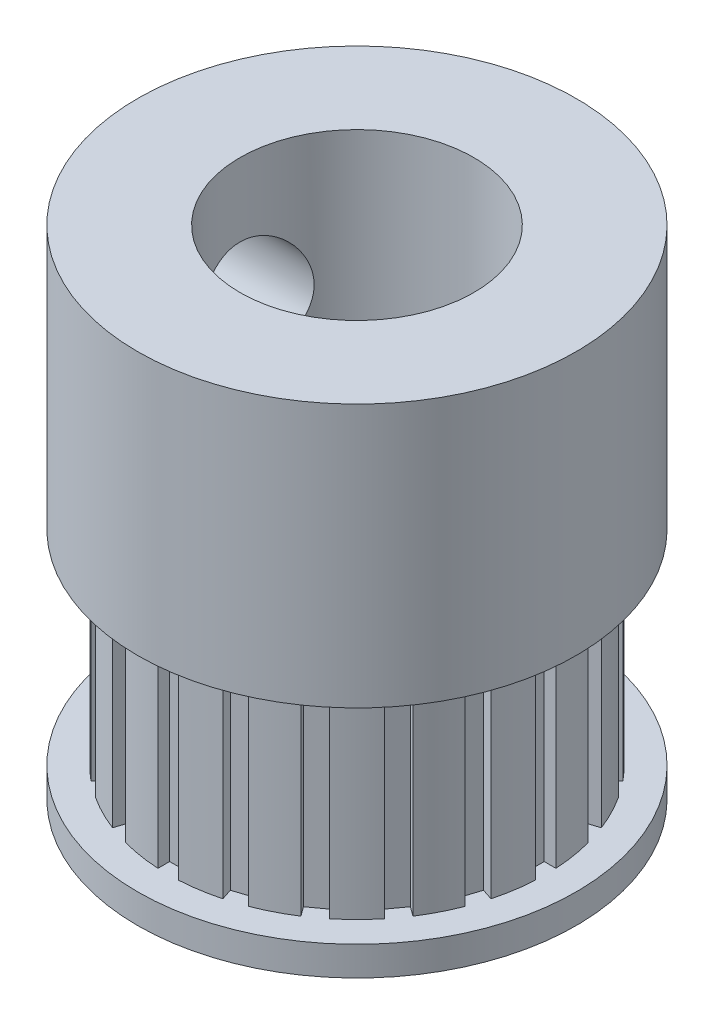
SolidWorks part; units mm, degrees
ref_plane "前视" through (0, 0, 0) normal (0, 0, 1) x (1, 0, 0)
ref_plane "上视" through (0, 0, 0) normal (0, 1, 0) x (1, 0, 0)
ref_plane "右视" through (0, 0, 0) normal (1, 0, 0) x (0, 0, -1)
sketch "草图1" plane through (0, 0, 0) normal (0, 1, 0) x (1, 0, 0)
  circle A0 centre (0, 0) radius 7.5
  dimension "D1" = 15
extrude "凸台-拉伸1" add sketch "草图1" along normal blind 1
sketch "草图2" plane through (0, 1, 0) normal (0, 1, 0) x (1, 0, 0)
  line L0 (-0.35, 6.4555) -> (-0.35, 6.0555)
  line L1 (0.35, 6.4555) -> (0.35, 6.0555)
  line L2 (0.35, 6.0555) -> (-0.35, 6.0555)
  line L3 (1.662, 6.2477) -> (1.5384, 5.8673)
  line L4 (2.2041, 5.651) -> (1.5384, 5.8673)
  line L5 (2.3277, 6.0314) -> (2.2041, 5.651)
  line L6 (3.5113, 5.4283) -> (3.2762, 5.1047)
  line L7 (3.8425, 4.6933) -> (3.2762, 5.1047)
  line L8 (4.0776, 5.0169) -> (3.8425, 4.6933)
  line L9 (5.0169, 4.0776) -> (4.6933, 3.8425)
  line L10 (5.1047, 3.2762) -> (4.6933, 3.8425)
  line L11 (5.4283, 3.5113) -> (5.1047, 3.2762)
  line L12 (6.0314, 2.3277) -> (5.651, 2.2041)
  line L13 (5.8673, 1.5384) -> (5.651, 2.2041)
  line L14 (6.2477, 1.662) -> (5.8673, 1.5384)
  line L15 (6.4555, 0.35) -> (6.0555, 0.35)
  line L16 (6.0555, -0.35) -> (6.0555, 0.35)
  line L17 (6.4555, -0.35) -> (6.0555, -0.35)
  line L18 (6.2477, -1.662) -> (5.8673, -1.5384)
  line L19 (5.651, -2.2041) -> (5.8673, -1.5384)
  line L20 (6.0314, -2.3277) -> (5.651, -2.2041)
  line L21 (5.4283, -3.5113) -> (5.1047, -3.2762)
  line L22 (4.6933, -3.8425) -> (5.1047, -3.2762)
  line L23 (5.0169, -4.0776) -> (4.6933, -3.8425)
  line L24 (4.0776, -5.0169) -> (3.8425, -4.6933)
  line L25 (3.2762, -5.1047) -> (3.8425, -4.6933)
  line L26 (3.5113, -5.4283) -> (3.2762, -5.1047)
  line L27 (2.3277, -6.0314) -> (2.2041, -5.651)
  line L28 (1.5384, -5.8673) -> (2.2041, -5.651)
  line L29 (1.662, -6.2477) -> (1.5384, -5.8673)
  line L30 (0.35, -6.4555) -> (0.35, -6.0555)
  line L31 (-0.35, -6.0555) -> (0.35, -6.0555)
  line L32 (-0.35, -6.4555) -> (-0.35, -6.0555)
  line L33 (-1.662, -6.2477) -> (-1.5384, -5.8673)
  line L34 (-2.2041, -5.651) -> (-1.5384, -5.8673)
  line L35 (-2.3277, -6.0314) -> (-2.2041, -5.651)
  line L36 (-3.5113, -5.4283) -> (-3.2762, -5.1047)
  line L37 (-3.8425, -4.6933) -> (-3.2762, -5.1047)
  line L38 (-4.0776, -5.0169) -> (-3.8425, -4.6933)
  line L39 (-5.0169, -4.0776) -> (-4.6933, -3.8425)
  line L40 (-5.1047, -3.2762) -> (-4.6933, -3.8425)
  line L41 (-5.4283, -3.5113) -> (-5.1047, -3.2762)
  line L42 (-6.0314, -2.3277) -> (-5.651, -2.2041)
  line L43 (-5.8673, -1.5384) -> (-5.651, -2.2041)
  line L44 (-6.2477, -1.662) -> (-5.8673, -1.5384)
  line L45 (-6.4555, -0.35) -> (-6.0555, -0.35)
  line L46 (-6.0555, 0.35) -> (-6.0555, -0.35)
  line L47 (-6.4555, 0.35) -> (-6.0555, 0.35)
  line L48 (-6.2477, 1.662) -> (-5.8673, 1.5384)
  line L49 (-5.651, 2.2041) -> (-5.8673, 1.5384)
  line L50 (-6.0314, 2.3277) -> (-5.651, 2.2041)
  line L51 (-5.4283, 3.5113) -> (-5.1047, 3.2762)
  line L52 (-4.6933, 3.8425) -> (-5.1047, 3.2762)
  line L53 (-5.0169, 4.0776) -> (-4.6933, 3.8425)
  line L54 (-4.0776, 5.0169) -> (-3.8425, 4.6933)
  line L55 (-3.2762, 5.1047) -> (-3.8425, 4.6933)
  line L56 (-3.5113, 5.4283) -> (-3.2762, 5.1047)
  line L57 (-2.3277, 6.0314) -> (-2.2041, 5.651)
  line L58 (-1.5384, 5.8673) -> (-2.2041, 5.651)
  line L59 (-1.662, 6.2477) -> (-1.5384, 5.8673)
  circle A0 centre (0, 0) radius 6.465
  point P85 (0, 0)
  dimension "D1" = 12.93
  dimension "D2" = 0.35
  dimension "D3" = 0.7
  dimension "D4" = 0.4
  dimension "D5" = 20
extrude "凸台-拉伸2" add sketch "草图2" along normal blind 7 contours L30 A0 L29 L28 L27 L26 L25 L24 L23 L22 L21 L20 L19 L18 L17 L16 L15 L14 L13 L12 L11 L10 L9 L8 L7 L6 L5 L4 L3 L1 L2 L0 L59 L58 L57 L56 L55 L54 L53
sketch "草图3" plane through (0, 8, 0) normal (0, 1, 0) x (1, 0, 0)
  circle A0 centre (0, 0) radius 7.5
  dimension "D1" = 15
extrude "凸台-拉伸3" add sketch "草图3" along normal blind 9
sketch "草图4" plane through (0, 17, 0) normal (0, 1, 0) x (1, 0, 0)
  circle A0 centre (0, 0) radius 4
  dimension "D1" = 8
extrude "切除-拉伸1" cut sketch "草图4" against normal up to next
sketch "草图5" plane through (0, 0, 0) normal (1, 0, 0) x (0, 0, -1)
  line L0 (7.5, 17) -> (-7.5, 17) construction
  circle A0 centre (0, 12.5) radius 2
  dimension "D1" = 4
  dimension "D2" = 4.5
extrude "切除-拉伸2" cut sketch "草图5" against normal up to next contours A0
cosmetic thread "装饰螺纹线1" parameters "D2"=4.5
